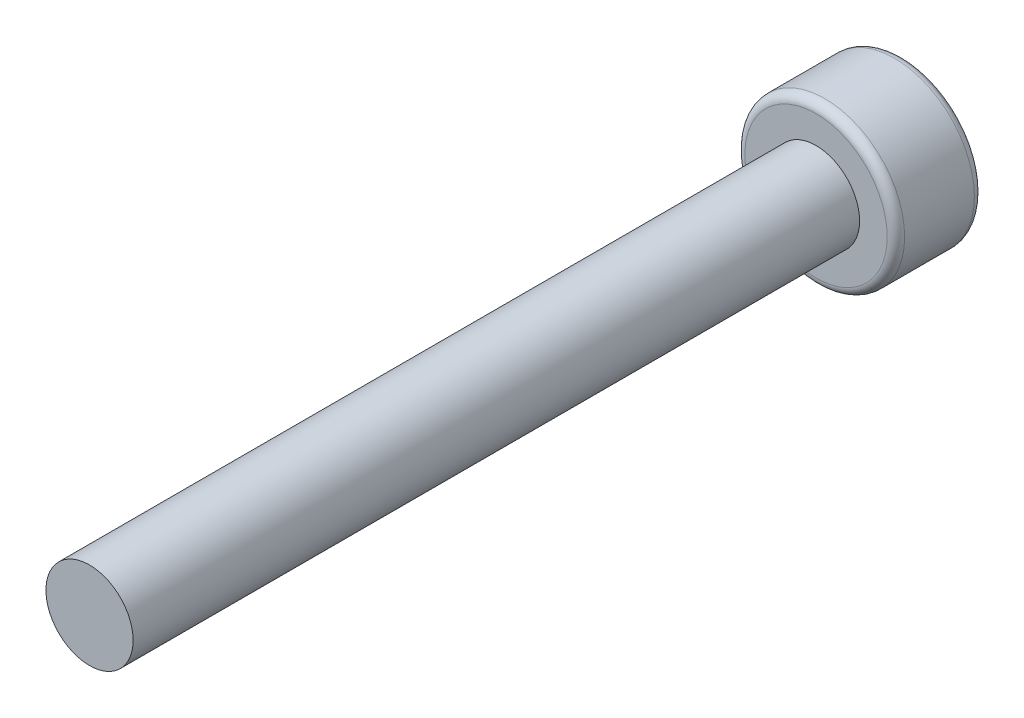
SolidWorks part; units mm, degrees
ref_plane "前视基准面" through (0, 0, 0) normal (0, 0, 1) x (1, 0, 0)
ref_plane "上视基准面" through (0, 0, 0) normal (0, 1, 0) x (1, 0, 0)
ref_plane "右视基准面" through (0, 0, 0) normal (1, 0, 0) x (0, 0, -1)
sketch "草图1" plane through (0, 0, 0) normal (0, 0, 1) x (1, 0, 0)
  circle A0 centre (0, 0) radius 2.75
  dimension "D1" = 2.75
extrude "凸台-拉伸1" add sketch "草图1" along normal blind 3
sketch "草图2" plane through (0, 0, 3) normal (0, 0, 1) x (1, 0, 0)
  circle A0 centre (0, 0) radius 1.5
  dimension "D1" = 1.5
extrude "凸台-拉伸2" add sketch "草图2" along normal blind 25
cosmetic thread "装饰螺纹线1" parameters "D2"=2
fillet "圆角1" radius 0.3 2 edges at (2.75, 0, 0) (2.75, 0, 3)
sketch "草图3" plane through (0, 0, 0) normal (0, 0, -1) x (-1, 0, 0)
  line L1 (-0.8209, 1.8624) -> (-2.0233, 0.2203)
  line L2 (-2.0233, 0.2203) -> (-1.2025, -1.6421)
  line L3 (-1.2025, -1.6421) -> (0.8209, -1.8624)
  line L4 (0.8209, -1.8624) -> (2.0233, -0.2203)
  line L5 (2.0233, -0.2203) -> (1.2025, 1.6421)
  line L6 (1.2025, 1.6421) -> (-0.8209, 1.8624)
  circle A0 centre (0, 0) radius 1.7626 construction
extrude "切除-拉伸1" cut sketch "草图3" against normal blind 2
